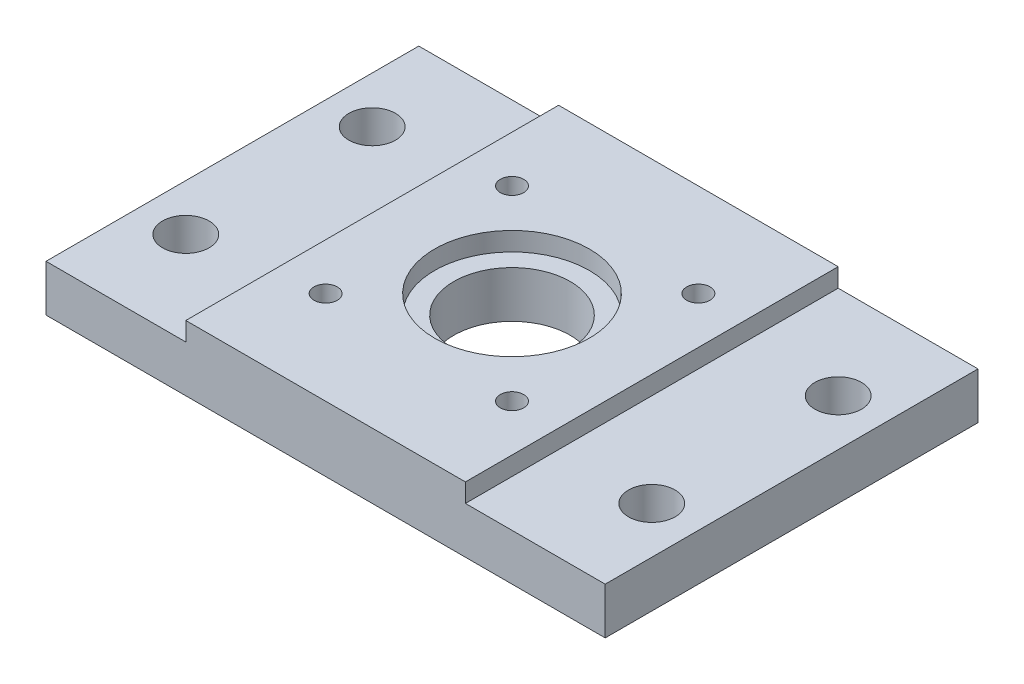
SolidWorks part; units mm, degrees
ref_plane "Front Plane" through (0, 0, 0) normal (0, 0, 1) x (1, 0, 0)
ref_plane "Top Plane" through (0, 0, 0) normal (0, 1, 0) x (1, 0, 0)
ref_plane "Right Plane" through (0, 0, 0) normal (1, 0, 0) x (0, 0, -1)
sketch "Sketch1" plane through (0, 0, 0) normal (0, 1, 0) x (1, 0, 0)
  line L0 (0, -1000) -> (0, 49000) construction
  line L1 (30, -20) -> (-30, -20)
  line L2 (30, -20) -> (30, 20)
  line L3 (30, 20) -> (-30, 20)
  line L4 (-30, -20) -> (-30, 20)
  line L5 (30, -20) -> (-30, 20) construction
  line L6 (30, 20) -> (-30, -20) construction
  circle A0 centre (25, 10) radius 2.5
  circle A1 centre (25, -10) radius 2.5
  circle A2 centre (0, 0) radius 6.25
  circle A3 centre (-25, -10) radius 2.5
  circle A4 centre (-25, 10) radius 2.5
  point P0 (0, 0)
  dimension "D4" = 5
  dimension "D8" = 12.5
  dimension "D1" = 60
  dimension "D2" = 40
  dimension "D3" = 5
  dimension "D5" = 20
  dimension "D6" = 10
extrude "Body" add sketch "Sketch1" along normal blind 5
sketch "Sketch3" plane through (0, 5, 0) normal (0, 1, 0) x (1, 0, 0)
  line L0 (-30, -20) -> (30, -20) construction
  line L1 (-15, 20) -> (15, 20)
  line L2 (-15, 20) -> (-15, -20)
  line L3 (-15, -20) -> (15, -20)
  line L4 (15, 20) -> (15, -20)
  line L5 (-15, 20) -> (15, -20) construction
  circle A0 centre (0, 0) radius 8.3
  dimension "D1" = 16.6
  dimension "D2" = 30
extrude "Bearing_Place" add sketch "Sketch3" along normal blind 2
sketch "Sketch4" plane through (0, 7, 0) normal (0, 1, 0) x (1, 0, 0)
  line L1 (10, -10) -> (-10, -10) construction
  line L2 (10, -10) -> (10, 10) construction
  line L3 (10, 10) -> (-10, 10) construction
  line L4 (-10, -10) -> (-10, 10) construction
  line L5 (10, -10) -> (-10, 10) construction
  line L6 (10, 10) -> (-10, -10) construction
  circle A0 centre (-10, 10) radius 1.25
  circle A1 centre (10, 10) radius 1.25
  circle A2 centre (10, -10) radius 1.25
  circle A3 centre (-10, -10) radius 1.25
  point P0 (0, 0)
  dimension "D1" = 2.5
  dimension "D3" = 20
extrude "Fixation_Holes" cut sketch "Sketch4" against normal through all
